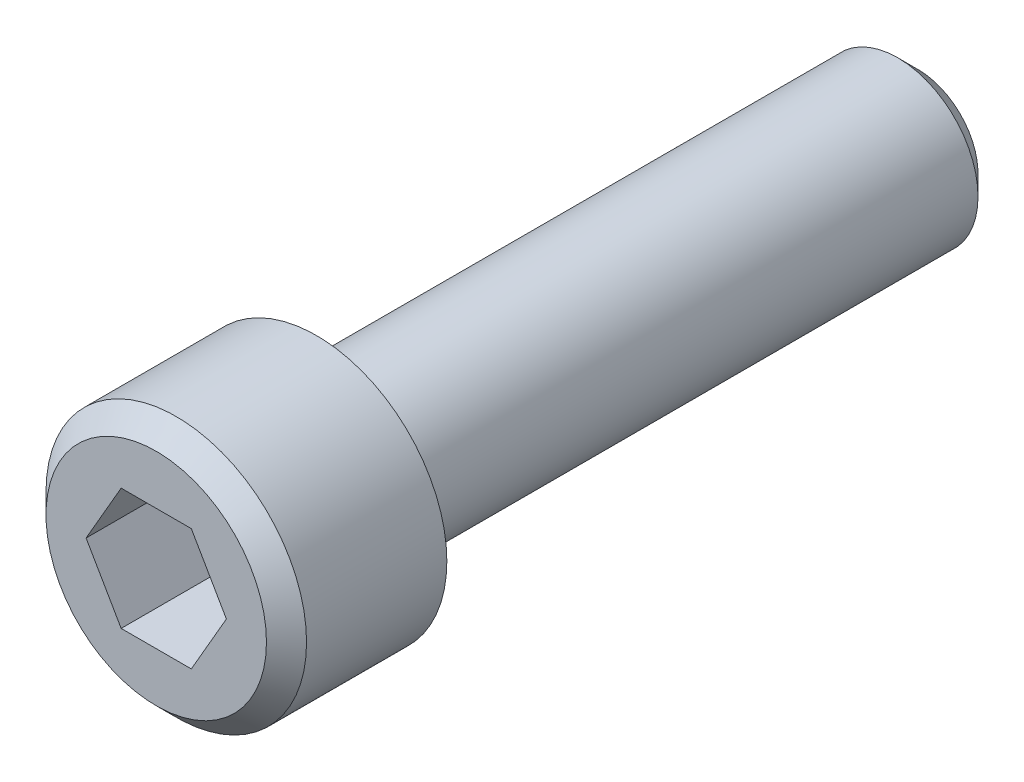
SolidWorks part; units mm, degrees
ref_plane "Alzado" through (0, 0, 0) normal (0, 0, 1) x (1, 0, 0)
ref_plane "Planta" through (0, 0, 0) normal (0, 1, 0) x (1, 0, 0)
ref_plane "Vista lateral" through (0, 0, 0) normal (1, 0, 0) x (0, 0, -1)
sketch "Croquis1" plane through (0, 0, 0) normal (0, 0, 1) x (1, 0, 0)
  circle A0 centre (0, 0) radius 6.5
  dimension "D1" = 13
extrude "Saliente-Extruir1" add sketch "Croquis1" along normal blind 8
sketch "Croquis2" plane through (0, 0, 0) normal (0, 0, -1) x (-1, 0, 0)
  circle A0 centre (0, 0) radius 4
  dimension "D1" = 8
extrude "Saliente-Extruir2" add sketch "Croquis2" along normal blind 30
chamfer "Chaflán1" distance 1 angle 45 2 edges at (6.5, 0, 8) (-4, 0, -30)
sketch "Croquis3" plane through (0, 0, 8) normal (0, 0, 1) x (1, 0, 0)
  line L1 (3.5, 0) -> (1.75, 3.0311)
  line L2 (1.75, 3.0311) -> (-1.75, 3.0311)
  line L3 (-1.75, 3.0311) -> (-3.5, 0)
  line L4 (-3.5, 0) -> (-1.75, -3.0311)
  line L5 (-1.75, -3.0311) -> (1.75, -3.0311)
  line L6 (1.75, -3.0311) -> (3.5, 0)
  circle A0 centre (0, 0) radius 3.0311 construction
  dimension "D1" = 7
extrude "Cortar-Extruir1" cut sketch "Croquis3" against normal blind 6
